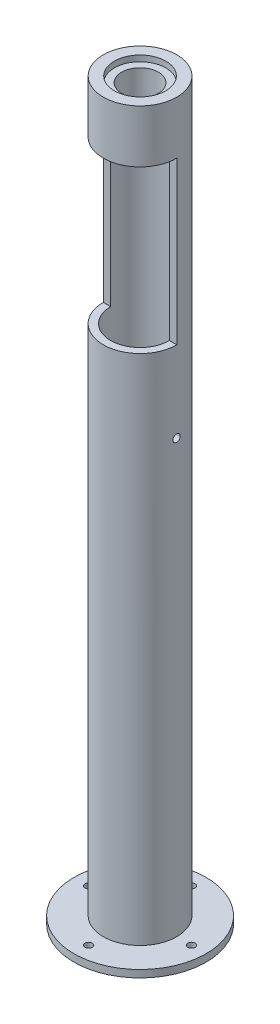
SolidWorks part; units mm, degrees
ref_plane "Front Plane" through (0, 0, 0) normal (0, 0, 1) x (1, 0, 0)
ref_plane "Top Plane" through (0, 0, 0) normal (0, 1, 0) x (1, 0, 0)
ref_plane "Right Plane" through (0, 0, 0) normal (1, 0, 0) x (0, 0, -1)
sketch "Sketch1" plane through (0, 0, 0) normal (0, 0, 1) x (1, 0, 0)
  line L0 (0, 0) -> (0, 98.5499) construction
  line L1 (20, 0) -> (45, 0)
  line L2 (45, 0) -> (45, 5)
  line L3 (45, 5) -> (25, 5)
  line L4 (25, 5) -> (25, 500)
  line L5 (25, 500) -> (17.5, 500)
  line L6 (17.5, 500) -> (17.5, 496)
  line L7 (17.5, 496) -> (12.5, 496)
  line L8 (12.5, 496) -> (12.5, 471)
  line L11 (12.5, 471) -> (6, 471)
  line L12 (6, 471) -> (6, 464)
  line L13 (6, 464) -> (20, 464)
  line L14 (20, 464) -> (20, 0)
  dimension "D1" = 12
  dimension "D2" = 35
  dimension "D3" = 50
  dimension "D4" = 5
  dimension "D5" = 90
  dimension "D6" = 4
  dimension "D7" = 25
  dimension "D8" = 500
  dimension "D9" = 25
  dimension "D10" = 40
  dimension "D11" = 7
revolve "Revolve1" add sketch "Sketch1" angle 360 about L0
ref_plane "Plane1" through (-25, 0, 0) normal (-1, 0, 0) x (0, 0, 1)
sketch "Sketch2" plane through (-25, 0, 0) normal (-1, 0, 0) x (0, 0, 1)
  line L0 (0, 464) -> (0, 354)
  line L1 (0, 354) -> (30, 354)
  line L2 (30, 354) -> (30, 464)
  line L3 (30, 464) -> (0, 464)
  line L4 (0, 0) -> (0, 160.2026) construction
  line L5 (-45, 0) -> (45, 0) construction
  line L6 (25, 500) -> (-25, 500) construction
  circle A0 centre (0, 299) radius 2.5
  dimension "D5" = 5
  dimension "D1" = 110
  dimension "D2" = 55
  dimension "D3" = 30
  dimension "D4" = 36
extrude "Cut-Extrude1" cut sketch "Sketch2" against normal through all
sketch "Sketch3" plane through (0, 471, 0) normal (0, 1, 0) x (1, 0, 0)
  circle A0 centre (0, 0) radius 10.07 construction
  circle A1 centre (-8.0908, 5.9953) radius 1.5
  circle A2 centre (7.4092, 6.8198) radius 1.5
  dimension "D1" = 20.14
  dimension "D3" = 3
  dimension "D2" = 15.5
extrude "Cut-Extrude2" cut sketch "Sketch3" against normal through all
sketch "Sketch4" plane through (0, 5, 0) normal (0, 1, 0) x (1, 0, 0)
  line L0 (0, 0) -> (0, 45) construction
  circle A0 centre (0, 0) radius 45 construction
  circle A1 centre (0, 35) radius 2.5
  circle A2 centre (35, 0) radius 2.5
  circle A3 centre (0, -35) radius 2.5
  circle A4 centre (-35, 0) radius 2.5
  point P8 (-35.7469, 3.2642)
  point P9 (0, 0)
  point P10 (0, 0)
  point P17 (40.0724, -5.0724)
  dimension "D2" = 5
  dimension "D1" = 35
  dimension "D3" = 4
extrude "Cut-Extrude3" cut sketch "Sketch4" against normal up to next
